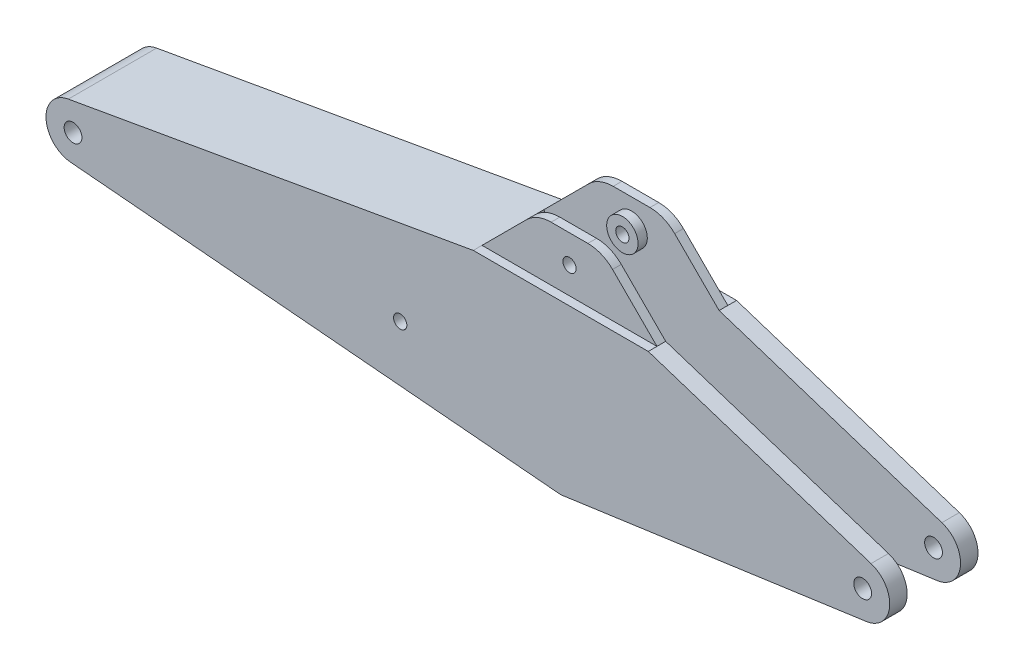
SolidWorks part; units mm, degrees
ref_plane "Front Plane" through (0, 0, 0) normal (0, 0, 1) x (1, 0, 0)
ref_plane "Top Plane" through (0, 0, 0) normal (0, 1, 0) x (1, 0, 0)
ref_plane "Right Plane" through (0, 0, 0) normal (1, 0, 0) x (0, 0, -1)
sketch "Sketch1" plane through (0, 0, 0) normal (0, 0, 1) x (1, 0, 0)
  line L0 (-4551.9221, 152.644) -> (-2231.2984, 561.9365)
  line L1 (-2231.2984, 561.9365) -> (-1976.8136, 816.4214)
  line L2 (-1835.3922, 875) -> (-1624.6078, 875)
  line L3 (-1483.1864, 816.4214) -> (-1228.7016, 561.9365)
  line L4 (-1228.7016, 561.9365) -> (47.8695, 147.4229)
  line L5 (21.6011, -153.4874) -> (-1730, -400)
  line L6 (-1730, -400) -> (-4538.5024, -154.4108)
  line L7 (-1730, -400) -> (-1730, 1534.6132) construction
  line L8 (-2231.2984, 561.9365) -> (-1228.7016, 561.9365) construction
  line L9 (-4525, 0) -> (0, 0) construction
  circle A0 centre (0, 0) radius 51
  arc A1 (21.6011, -153.4874) -> (47.8695, 147.4229) centre (0, 0) ccw
  circle A2 centre (-2650, 0) radius 38
  circle A3 centre (-4525, 0) radius 51
  arc A4 (-4551.9221, 152.644) -> (-4538.5024, -154.4108) centre (-4525, 0) ccw
  circle A5 centre (-1730, 714.9365) radius 38
  arc A6 (-1624.6078, 875) -> (-1483.1864, 816.4214) centre (-1624.6078, 675) cw
  arc A7 (-1976.8136, 816.4214) -> (-1835.3922, 875) centre (-1835.3922, 675) cw
  circle A8 centre (-1730, 714.9365) radius 90 construction
  dimension "D1" = 102
  dimension "D2" = 155
  dimension "D11" = 200
  dimension "D13" = 76
  dimension "D15" = 76
  dimension "D12" = 180
  dimension "D3" = 875
  dimension "D4" = 153
  dimension "D5" = 2795
  dimension "D6" = 26
  dimension "D7" = 15
  dimension "D8" = 4525
  dimension "D9" = 45
  dimension "D10" = 400
  dimension "D14" = 2650
extrude "Boss-Extrude2" add sketch "Sketch1" along normal mid plane 506 contours L0 L1 A7 L2 A6 L3 L4 A1 L5 L6 A4
sketch "Sketch2" plane through (0, 0, 0) normal (0, 0, 1) x (1, 0, 0)
  line L0 (0, 0) -> (-3405.0854, 0) construction
  line L14 (-2224.3508, 522.5445) -> (-2231.2984, 561.9365)
  line L15 (-706, -255.8868) -> (-711.5745, -216.2771)
  line L16 (-2231.2984, 561.9365) -> (-2231.2984, 1101.816)
  line L23 (-2231.2984, 1101.816) -> (280.4079, 1101.816)
  line L24 (280.4079, 1101.816) -> (280.4079, -255.8868)
  line L25 (280.4079, -255.8868) -> (-706, -255.8868)
  line L26 (-1730, -400) -> (21.6011, -153.4874) construction
  line L28 (-1731.0586, -359.7548) -> (16.0267, -113.8778)
  line L29 (-4535.0179, -114.5628) -> (-1731.0586, -359.7548)
  line L30 (-2224.3508, 522.5445) -> (-4544.9745, 113.252)
  line L31 (-1731.0586, -359.7548) -> (-711.5745, -216.2771)
  line L32 (-4535.0179, -114.5628) -> (-1731.0586, -359.7548)
  line L33 (-2224.3508, 522.5445) -> (-4544.9745, 113.252)
  arc A4 (-4544.9745, 113.252) -> (-4535.0179, -114.5628) centre (-4525, 0) ccw
  arc A5 (-4544.9745, 113.252) -> (-4535.0179, -114.5628) centre (-4525, 0) ccw
  dimension "D1" = 706
  dimension "D2" = 40
extrude "Cut-Extrude1" cut sketch "Sketch2" against normal mid plane 306
sketch "Sketch3" plane through (0, 0, 253) normal (0, 0, 1) x (1, 0, 0)
  line L0 (-2231.2984, 561.9365) -> (-1228.7016, 561.9365)
  line L1 (-1228.7016, 561.9365) -> (-1228.7016, 1036.8065)
  line L2 (-1228.7016, 1036.8065) -> (-2231.2984, 1036.8065)
  line L3 (-2231.2984, 1036.8065) -> (-2231.2984, 561.9365)
extrude "Cut-Extrude3" cut sketch "Sketch3" against normal blind 50
mirror "Mirror2" about plane through (0, 0, 0) normal (0, 0, 1) of "Cut-Extrude3"
sketch "Sketch4" plane through (0, 0, -153) normal (0, 0, 1) x (1, 0, 0)
  circle A0 centre (-1730, 714.9365) radius 90
  circle A1 centre (-2650, 0) radius 90
  circle A2 centre (-2650, 0) radius 38 construction
  circle A3 centre (-1730, 714.9365) radius 38 construction
  circle A4 centre (-2650, 0) radius 38
  circle A5 centre (-1730, 714.9365) radius 38
  dimension "D1" = 180
extrude "Boss-Extrude3" add sketch "Sketch4" along normal blind 53
mirror "Mirror3" about plane through (0, 0, 0) normal (0, 0, 1) of "Boss-Extrude3"
